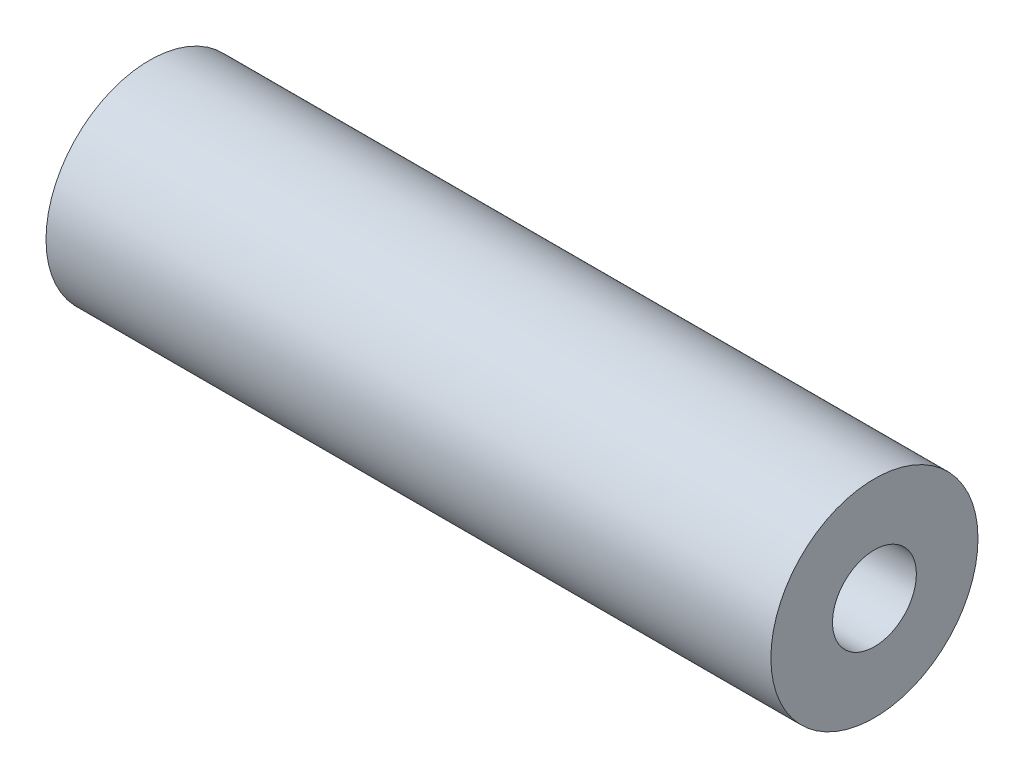
SolidWorks part; units mm, degrees
ref_plane "Front Plane" through (0, 0, 0) normal (0, 0, 1) x (1, 0, 0)
ref_plane "Top Plane" through (0, 0, 0) normal (0, 1, 0) x (1, 0, 0)
ref_plane "Right Plane" through (0, 0, 0) normal (1, 0, 0) x (0, 0, -1)
sketch "Sketch1" plane through (0, 0, 0) normal (1, 0, 0) x (0, 0, -1)
  circle A0 centre (0, 0) radius 20
  circle A1 centre (0, 0) radius 8.1
  dimension "D1" = 40
  dimension "D2" = 16.2
extrude "Boss-Extrude1" add sketch "Sketch1" along normal blind 140
